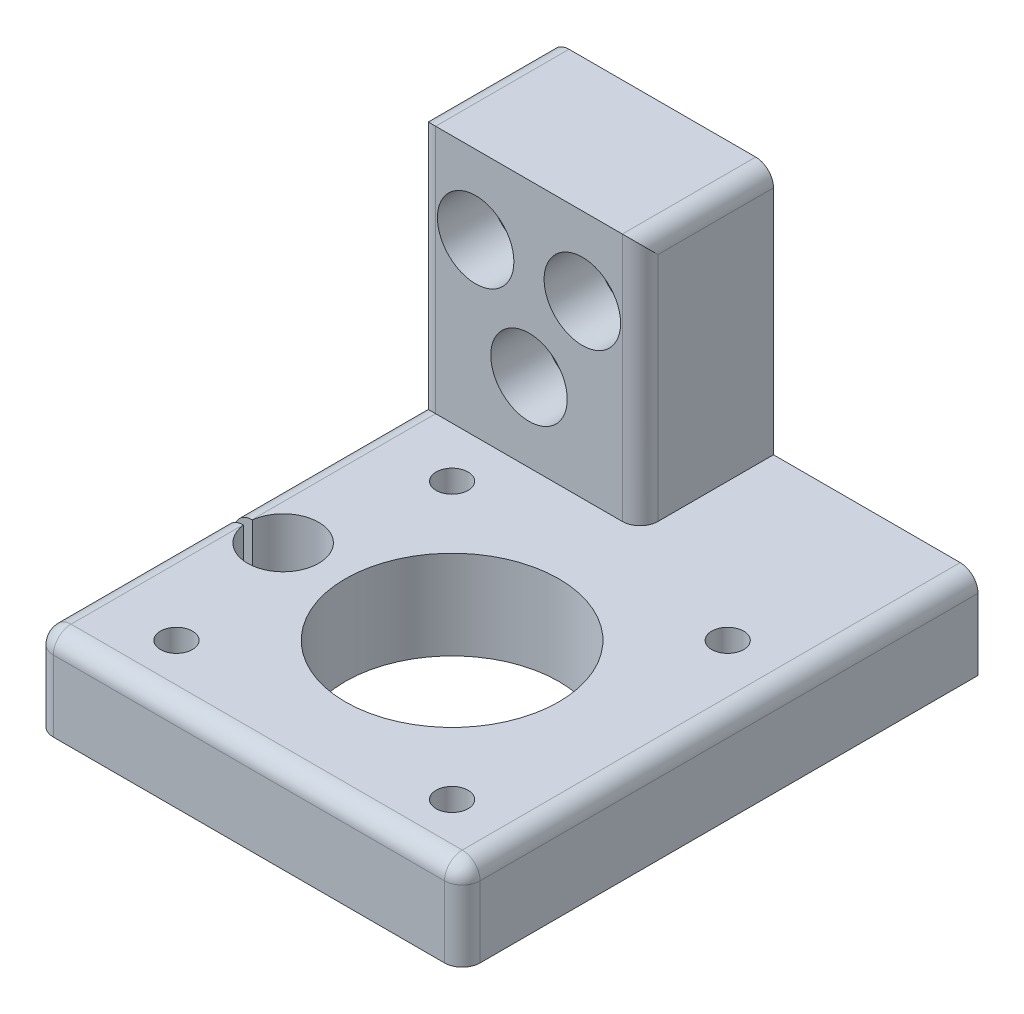
SolidWorks part; units mm, degrees
ref_plane "Front Plane" through (0, 0, 0) normal (0, 0, 1) x (1, 0, 0)
ref_plane "Top Plane" through (0, 0, 0) normal (0, 1, 0) x (1, 0, 0)
ref_plane "Right Plane" through (0, 0, 0) normal (1, 0, 0) x (0, 0, -1)
sketch "Sketch1" plane through (0, 0, 0) normal (0, 1, 0) x (1, 0, 0)
  line L0 (9.5, -20.65) -> (40.5, -20.65) construction
  line L1 (0, 0) -> (48, 0)
  line L2 (0, 0) -> (0, -58)
  line L3 (0, -58) -> (48, -58)
  line L4 (48, 0) -> (48, -58)
  line L5 (40.5, -20.65) -> (40.5, -51.65) construction
  line L6 (40.5, -51.65) -> (9.5, -51.65) construction
  line L7 (9.5, -51.65) -> (9.5, -20.65) construction
  line L8 (25, -36.15) -> (6, -36.15) construction
  line L9 (6, -36.15) -> (0, -36.15) construction
  line L11 (0, -35.65) -> (2.0314, -35.65)
  line L12 (0, -35.65) -> (0, -36.65)
  line L13 (0, -36.65) -> (2.0314, -36.65)
  line L14 (2.0314, -35.65) -> (2.0314, -36.65)
  circle A0 centre (9.5, -20.65) radius 1.8
  circle A1 centre (40.5, -20.65) radius 1.8
  circle A2 centre (40.5, -51.65) radius 1.8
  circle A3 centre (9.5, -51.65) radius 1.8
  circle A4 centre (25, -36.15) radius 12
  circle A5 centre (6, -36.15) radius 4
  dimension "D3" = 31
  dimension "D4" = 3.6
  dimension "D7" = 8
  dimension "D8" = 24
  dimension "D1" = 58
  dimension "D2" = 48
  dimension "D5" = 6.35
  dimension "D6" = 7.5
  dimension "D9" = 23
  dimension "D10" = 21.85
  dimension "D11" = 19
  dimension "D12" = 1
extrude "Boss-Extrude1" add sketch "Sketch1" along normal blind 10 contours A5 L11 L4 L1 L2 L3 L13 A4 A3 A2 A1 A0
sketch "Sketch2" plane through (0, 0, 0) normal (1, 0, 0) x (0, 0, -1)
  line L1 (0, 10) -> (-15, 10)
  line L2 (0, 10) -> (0, 38)
  line L3 (0, 38) -> (-15, 38)
  line L4 (-15, 10) -> (-15, 38)
  dimension "D1" = 28
  dimension "D2" = 15
extrude "Boss-Extrude2" add sketch "Sketch2" along normal blind 25
sketch "Sketch3" plane through (0, 0, 15) normal (0, 0, 1) x (1, 0, 0)
  line L0 (6.5, 29.1962) -> (18.5, 29.1962) construction
  line L1 (18.5, 29.1962) -> (12.5, 18.8038) construction
  line L2 (12.5, 18.8038) -> (6.5, 29.1962) construction
  line L3 (12.5, 18.8038) -> (12.5, 10) construction
  line L4 (25, 10) -> (0, 10) construction
  line L5 (12.5, 29.1962) -> (12.5, 38) construction
  line L6 (25, 38) -> (0, 38) construction
  circle A0 centre (6.5, 29.1962) radius 2.8
  circle A1 centre (18.5, 29.1962) radius 2.8
  circle A2 centre (12.5, 18.8038) radius 2.8
  dimension "D1" = 12
  dimension "D2" = 5.6
extrude "Cut-Extrude1" cut sketch "Sketch3" against normal through all contours A0
sketch "Sketch4" plane through (0, 0, 15) normal (0, 0, 1) x (1, 0, 0)
  circle A0 centre (6.5, 29.1962) radius 4.3
  circle A1 centre (18.5, 29.1962) radius 4.3
  circle A2 centre (12.5, 18.8038) radius 4.3
  dimension "D1" = 8.6
extrude "Cut-Extrude2" cut sketch "Sketch4" against normal blind 6
fillet "Fillet1" radius 2 10 edges at (48, 5, 58) (0, 5, 58) (0, 10, 47.325) (24, 10, 58) (48, 10, 29) (0, 24, 15) (25, 24, 15) (0, 38, 7.5) (25, 38, 7.5) (0, 10, 25.325)
